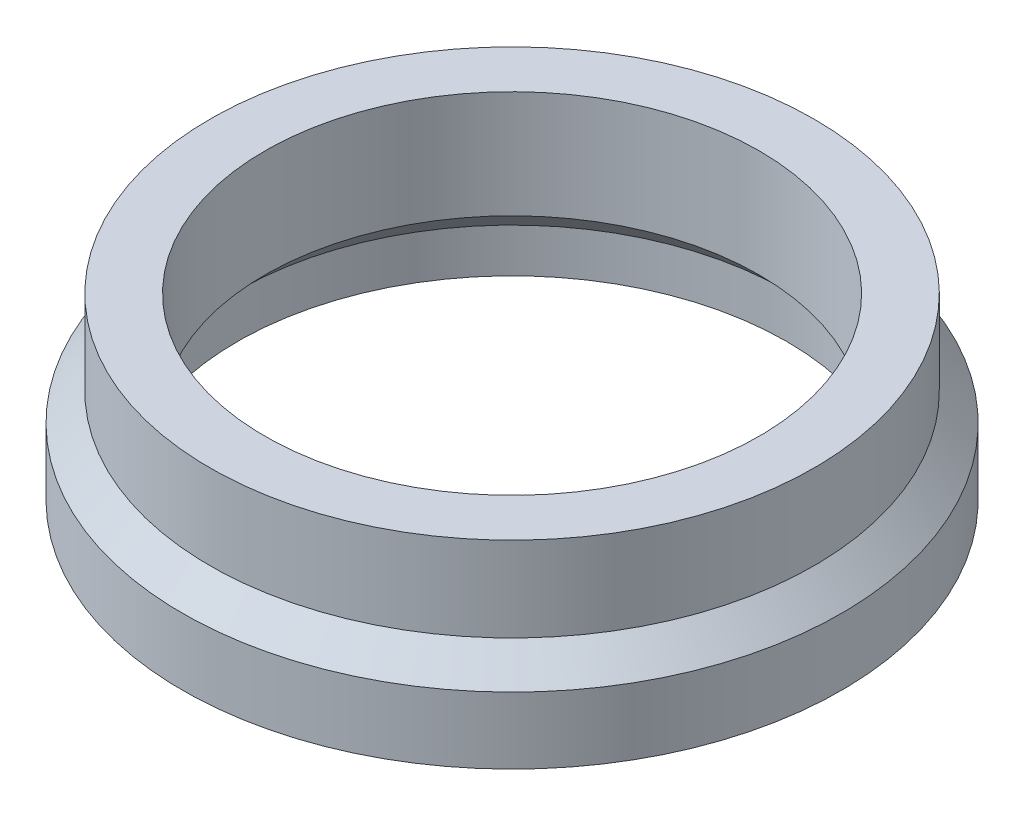
SolidWorks part; units mm, degrees
ref_plane "Front Plane" through (0, 0, 0) normal (0, 0, 1) x (1, 0, 0)
ref_plane "Top Plane" through (0, 0, 0) normal (0, 1, 0) x (1, 0, 0)
ref_plane "Right Plane" through (0, 0, 0) normal (1, 0, 0) x (0, 0, -1)
sketch "Sketch3" plane through (0, 0, 0) normal (0, 0, 1) x (1, 0, 0)
  line L0 (-6, 0) -> (-6, 1.2142)
  line L2 (-5.5, 1.7142) -> (-5.5, 3.2564)
  line L3 (-5.5, 3.2564) -> (-4.5, 3.2564)
  line L4 (-4.5, 3.2564) -> (-4.5, 1.3)
  line L6 (-5, 0.8) -> (-5, 0)
  line L7 (-5, 0) -> (-6, 0)
  line L8 (-5, 0) -> (0, 0) construction
  line L9 (-5.5, 1.7142) -> (-6, 1.2142)
  line L11 (0, 0) -> (0, 4.9107) construction
  line L12 (-5, 0.8) -> (-4.5, 1.3)
  line L13 (-5, 0.8) -> (-5, 1.3) construction
  line L14 (-5, 1.3) -> (-4.5, 1.3) construction
  line L15 (-5.5, 1.7142) -> (-4.7929, 1.0071) construction
  dimension "D1" = 1
  dimension "D2" = 4.5
  dimension "D3" = 5
  dimension "D4" = 0.8
revolve "Revolve1" add sketch "Sketch3" angle 360 about L11
